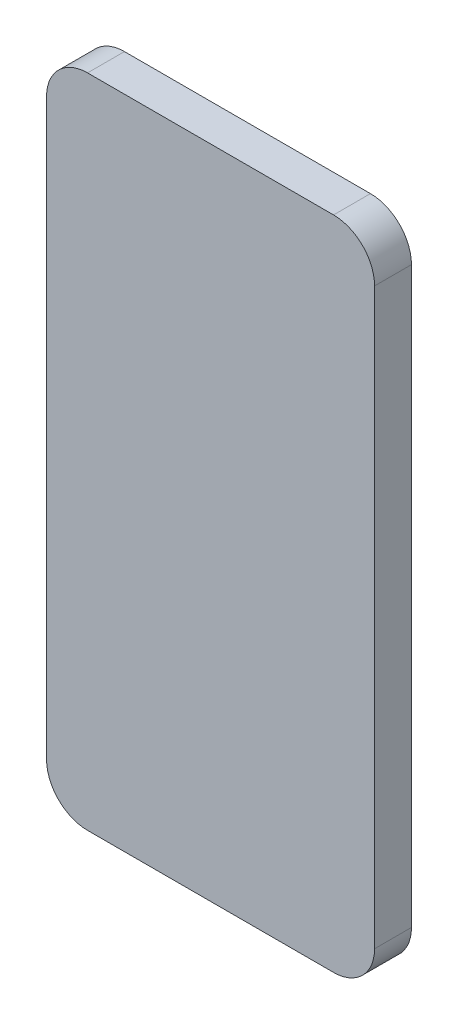
SolidWorks part; units mm, degrees
ref_plane "前视基准面" through (0, 0, 0) normal (0, 0, 1) x (1, 0, 0)
ref_plane "上视基准面" through (0, 0, 0) normal (0, 1, 0) x (1, 0, 0)
ref_plane "右视基准面" through (0, 0, 0) normal (1, 0, 0) x (0, 0, -1)
sketch "草图1" plane through (0, 0, 0) normal (0, 0, 1) x (1, 0, 0)
  line L1 (-39.1736, 40.6612) -> (40.8264, 40.6612)
  line L2 (-39.1736, 40.6612) -> (-39.1736, -119.3388)
  line L3 (-39.1736, -119.3388) -> (40.8264, -119.3388)
  line L4 (40.8264, 40.6612) -> (40.8264, -119.3388)
  dimension "D1" = 80
  dimension "D2" = 160
extrude "凸台-拉伸1" add sketch "草图1" along normal blind 9
fillet "圆角1" radius 10 1 edges at (-39.1736, 40.6612, 4.5)
fillet "圆角2" radius 10 1 edges at (40.8264, 40.6612, 4.5)
fillet "圆角3" radius 10 1 edges at (40.8264, -119.3388, 4.5)
fillet "圆角4" radius 10 1 edges at (-39.1736, -119.3388, 4.5)
